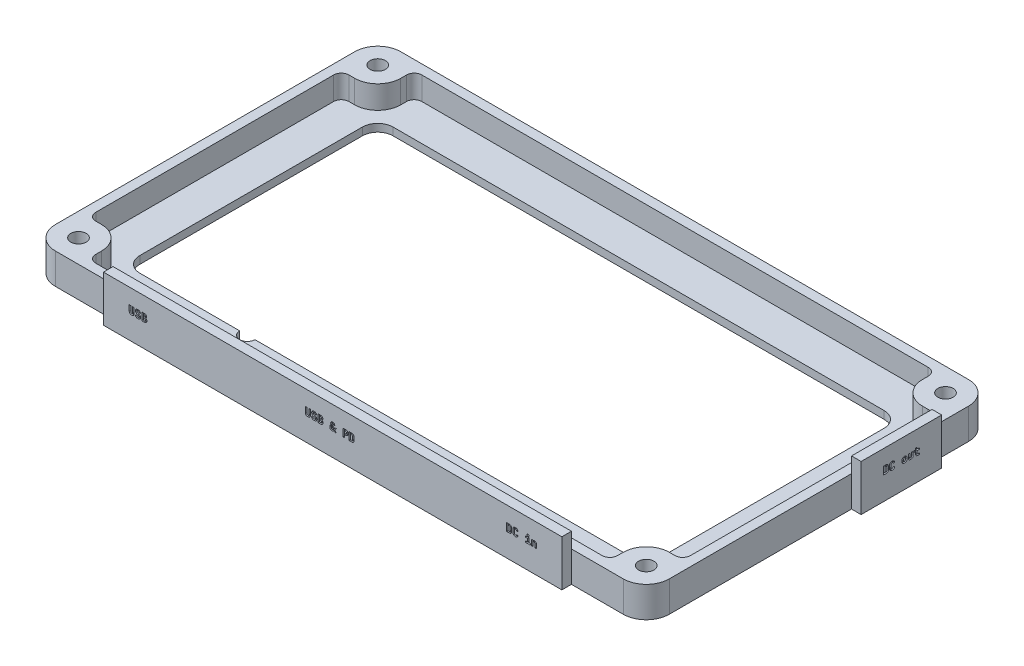
SolidWorks part; units mm, degrees
ref_plane "前视基准面" through (0, 0, 0) normal (0, 0, 1) x (1, 0, 0)
ref_plane "上视基准面" through (0, 0, 0) normal (0, 1, 0) x (1, 0, 0)
ref_plane "右视基准面" through (0, 0, 0) normal (1, 0, 0) x (0, 0, -1)
other "Configuration Table"
sketch "草图2" plane through (0, 0, 0) normal (0, 1, 0) x (1, 0, 0)
  line L1 (3, 0) -> (77, 0)
  line L2 (0, -3) -> (0, -42)
  line L3 (3, -45) -> (77, -45)
  line L4 (80, -3) -> (80, -42)
  arc A0 (77, -45) -> (80, -42) centre (77, -42) ccw
  arc A1 (0, -42) -> (3, -45) centre (3, -42) ccw
  arc A2 (3, 0) -> (0, -3) centre (3, -3) ccw
  arc A3 (77, 0) -> (80, -3) centre (77, -3) cw
  point P11 (0, 0)
  dimension "D1" = 3
extrude "凸台-拉伸1" add sketch "草图2" along normal blind 1
sketch "草图3" plane through (0, 1, 0) normal (0, 1, 0) x (1, 0, 0)
  line L0 (6, -3) -> (6, -2.25)
  line L2 (74, -3) -> (74, -2.25)
  line L3 (74, 0) -> (77, 0)
  line L5 (77, -6) -> (77.75, -6)
  line L8 (80, -6) -> (80, -3)
  line L10 (0, -3) -> (0, -6)
  line L11 (2.25, -6) -> (3, -6)
  line L13 (3, 0) -> (6, 0)
  line L17 (3, -39) -> (2.25, -39)
  line L20 (0, -39) -> (0, -42)
  line L22 (6, -42) -> (6, -42.75)
  line L23 (6, -45) -> (3, -45)
  line L26 (74, -42) -> (74, -42.75)
  line L27 (74, -45) -> (77, -45)
  line L29 (77, -39) -> (77.75, -39)
  line L32 (80, -39) -> (80, -42)
  line L33 (6, 0) -> (74, 0)
  line L35 (7, -1.25) -> (73, -1.25)
  line L38 (6, -45) -> (74, -45)
  line L40 (7, -43.75) -> (73, -43.75)
  line L43 (0, -6) -> (0, -39)
  line L45 (1.25, -7) -> (1.25, -38)
  line L47 (80, -6) -> (80, -39)
  line L49 (78.75, -7) -> (78.75, -38)
  arc A0 (3, -6) -> (6, -3) centre (3, -3) ccw
  arc A1 (0, -42) -> (3, -45) centre (3, -42) ccw
  arc A2 (77, -45) -> (80, -42) centre (77, -42) ccw
  arc A3 (74, -3) -> (77, -6) centre (77, -3) ccw
  arc A4 (3, 0) -> (0, -3) centre (3, -3) ccw
  arc A5 (80, -3) -> (77, 0) centre (77, -3) ccw
  arc A6 (77, -39) -> (74, -42) centre (77, -42) ccw
  arc A7 (6, -42) -> (3, -39) centre (3, -42) ccw
  arc A8 (6, -42.75) -> (7, -43.75) centre (7, -42.75) ccw
  arc A9 (2.25, -39) -> (1.25, -38) centre (2.25, -38) cw
  arc A10 (77.75, -39) -> (78.75, -38) centre (77.75, -38) ccw
  arc A11 (73, -43.75) -> (74, -42.75) centre (73, -42.75) ccw
  arc A12 (77.75, -6) -> (78.75, -7) centre (77.75, -7) cw
  arc A13 (73, -1.25) -> (74, -2.25) centre (73, -2.25) cw
  arc A14 (6, -2.25) -> (7, -1.25) centre (7, -2.25) cw
  arc A15 (2.25, -6) -> (1.25, -7) centre (2.25, -7) ccw
  dimension "D1" = 1
extrude "凸台-拉伸2" add sketch "草图3" along normal blind 3
sketch "草图5" plane through (0, 0, 0) normal (0, -1, 0) x (1, 0, 0)
  circle A0 centre (3, 42) radius 1
  circle A1 centre (3, 3) radius 1
  circle A2 centre (77, 3) radius 1
  circle A3 centre (77, 42) radius 1
extrude "切除-拉伸1" cut sketch "草图5" against normal up to next
sketch "草图6" plane through (0, 0, 0) normal (0, -1, 0) x (1, 0, 0)
  circle A0 centre (3, 42) radius 2
  circle A1 centre (3, 3) radius 2
  circle A2 centre (77, 42) radius 2
  circle A3 centre (77, 3) radius 2
extrude "切除-拉伸2" cut sketch "草图6" against normal blind 1.5
sketch "草图7" plane through (0, 0, 0) normal (0, -1, 0) x (1, 0, 0)
  line L1 (3, 45) -> (77, 45) construction
  line L3 (80, 45) -> (80, 13) construction
  line L4 (10.5, 45) -> (70.25, 45)
  line L5 (10.5, 45) -> (10.5, 46.25)
  line L6 (10.5, 46.25) -> (70.25, 46.25)
  line L7 (70.25, 45) -> (70.25, 46.25)
  line L8 (80, 42) -> (80, 3) construction
  line L11 (80, 18.25) -> (81.25, 18.25)
  line L12 (80, 18.25) -> (80, 7.75)
  line L13 (80, 7.75) -> (81.25, 7.75)
  line L14 (81.25, 18.25) -> (81.25, 7.75)
  point P15 (80, 13)
extrude "凸台-拉伸3" add sketch "草图7" against normal blind 6
sketch "草图9" plane through (0, 0, 0) normal (0, -1, 0) x (1, 0, 0)
  line L1 (8, 39) -> (72, 39)
  line L2 (6, 37) -> (6, 8)
  line L3 (8, 6) -> (72, 6)
  line L4 (74, 37) -> (74, 8)
  circle A0 centre (3, 42) radius 3 construction
  circle A1 centre (3, 3) radius 3 construction
  circle A2 centre (77, 3) radius 3 construction
  circle A3 centre (77, 42) radius 3 construction
  arc A4 (6, 8) -> (8, 6) centre (8, 8) ccw
  arc A5 (72, 6) -> (74, 8) centre (72, 8) ccw
  arc A6 (72, 39) -> (74, 37) centre (72, 37) cw
  arc A7 (8, 39) -> (6, 37) centre (8, 37) ccw
  dimension "D1" = 2
extrude "切除-拉伸3" cut sketch "草图9" against normal up to next
sketch "草图10" plane through (0, 0, 46.25) normal (0, 0, 1) x (1, 0, 0)
  line L0 (0, 3) -> (80, 3) construction
  line L1 (11.4624, 3) -> (18.5376, 3) construction
  line L2 (0, 3) -> (15, 3) construction
  line L3 (80, 4) -> (80, 0) construction
  line L4 (80, 3) -> (65, 3) construction
  line L5 (60.4445, 3) -> (69.5555, 3) construction
  text T0 "USB" font "JetBrains Mono ExtraBold" height 1
  text T1 "USB & PD" font "JetBrains Mono ExtraBold" height 1
  text T2 "DC in" font "JetBrains Mono ExtraBold" height 1
  point P7 (15, 3)
  point P13 (65, 3)
extrude "切除-拉伸4" cut sketch "草图10" against normal blind 0.2
sketch "草图11" plane through (81.25, 0, 0) normal (1, 0, 0) x (0, 0, -1)
  line L0 (-18.25, 3) -> (-7.75, 3) construction
  line L1 (-18.25, 6) -> (-18.25, 0) construction
  line L2 (-7.75, 6) -> (-7.75, 0) construction
  text T0 "DC out" font "JetBrains Mono ExtraBold" height 1
extrude "切除-拉伸5" cut sketch "草图11" against normal blind 0.2
sketch "草图12" plane through (0, 1, 0) normal (0, 1, 0) x (1, 0, 0)
  line L10 (72, -39) -> (8, -39) construction
  line L11 (80, -45) -> (22, -45) construction
  line L12 (80, -45) -> (80, -39) construction
  line L13 (80, -39) -> (22, -39) construction
  line L14 (22, -45) -> (22, -39) construction
  circle A0 centre (22, -39) radius 1
  point P0 (80, -45)
extrude "切除-拉伸6" cut sketch "草图12" against normal up to next
